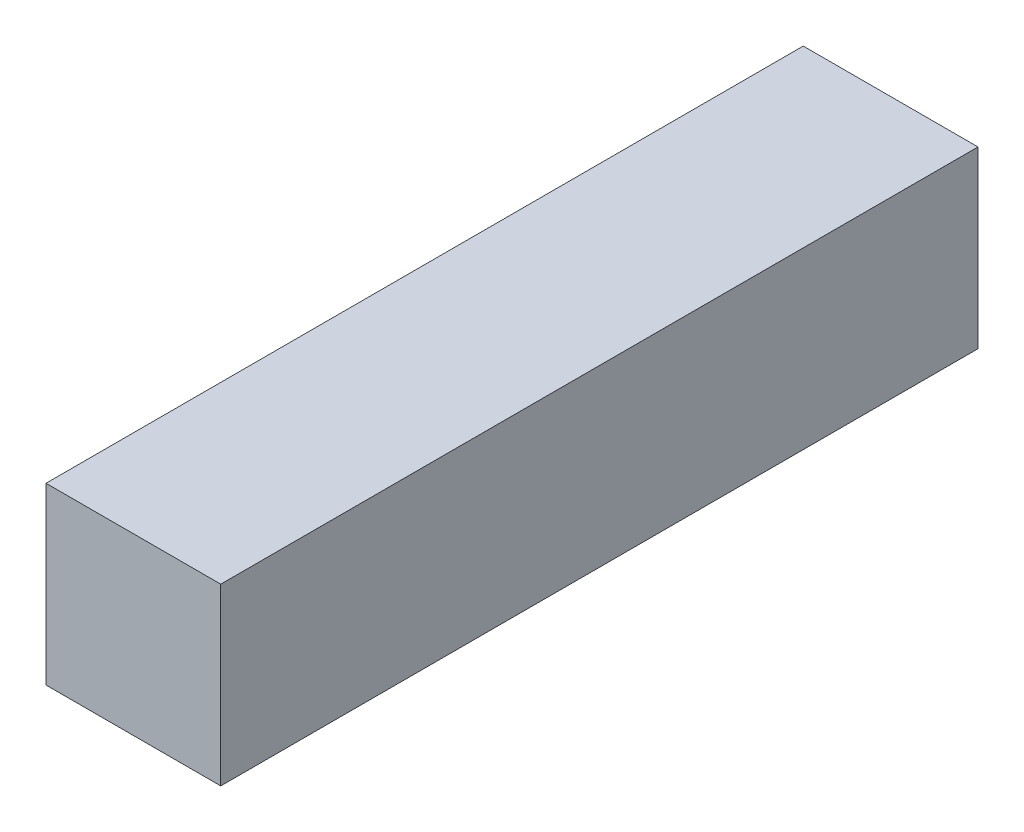
SolidWorks part; units mm, degrees
ref_plane "Plan de face" through (0, 0, 0) normal (0, 0, 1) x (1, 0, 0)
ref_plane "Plan de dessus" through (0, 0, 0) normal (0, 1, 0) x (1, 0, 0)
ref_plane "Plan de droite" through (0, 0, 0) normal (1, 0, 0) x (0, 0, -1)
sketch "Esquisse1" plane through (0, 0, 0) normal (0, 0, 1) x (1, 0, 0)
  line L1 (-74.0742, 30.5952) -> (-44.0742, 30.5952)
  line L2 (-74.0742, 30.5952) -> (-74.0742, 0.5952)
  line L3 (-74.0742, 0.5952) -> (-44.0742, 0.5952)
  line L4 (-44.0742, 30.5952) -> (-44.0742, 0.5952)
  dimension "D1" = 30
extrude "Boss.-Extru.1" add sketch "Esquisse1" along normal blind 130
